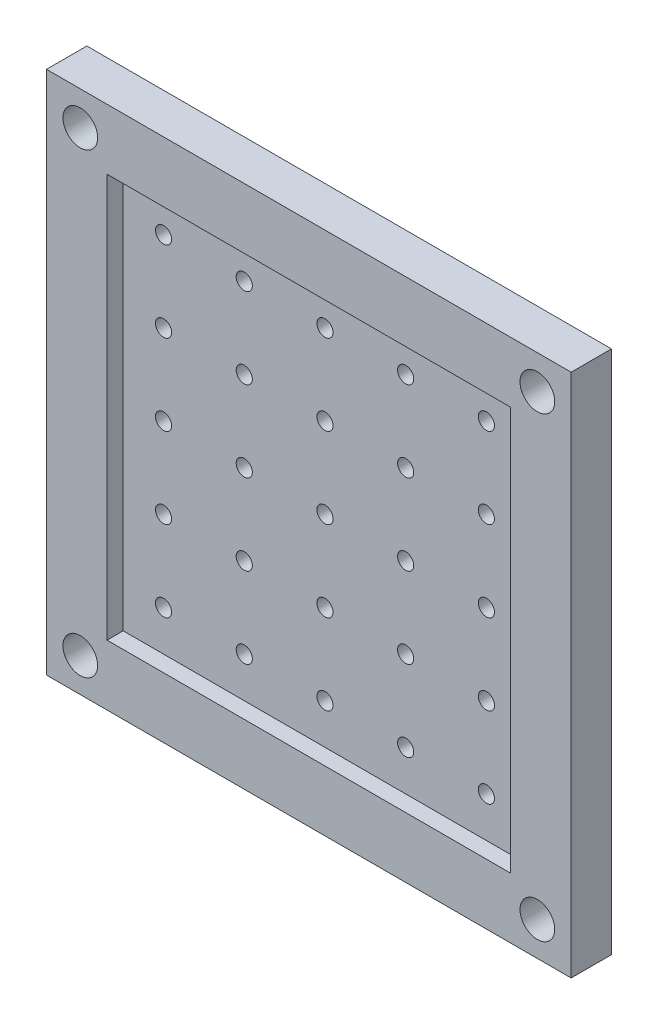
SolidWorks part; units mm, degrees
ref_plane "Front Plane" through (0, 0, 0) normal (0, 0, 1) x (1, 0, 0)
ref_plane "Top Plane" through (0, 0, 0) normal (0, 1, 0) x (1, 0, 0)
ref_plane "Right Plane" through (0, 0, 0) normal (1, 0, 0) x (0, 0, -1)
sketch "Sketch1" plane through (0, 0, 0) normal (0, 0, 1) x (1, 0, 0)
  line L1 (-32.5, -32.5) -> (32.5, -32.5)
  line L2 (-32.5, -32.5) -> (-32.5, 32.5)
  line L3 (-32.5, 32.5) -> (32.5, 32.5)
  line L4 (32.5, -32.5) -> (32.5, 32.5)
  line L5 (-32.5, -32.5) -> (32.5, 32.5) construction
  line L6 (-32.5, 32.5) -> (32.5, -32.5) construction
  line L7 (35, 35) -> (-35, 35) construction
  circle A9 centre (-28.3137, 28.3137) radius 2.15
  circle A10 centre (-28.3137, -28.3137) radius 2.15
  circle A11 centre (28.3137, -28.3137) radius 2.15
  circle A12 centre (28.3137, 28.3137) radius 2.15
  circle A13 centre (-28.3137, 28.3137) radius 1.85 construction
  point P0 (0, 0)
  dimension "D2" = 0.3
  dimension "D1" = 2.5
extrude "Boss-Extrude1" add sketch "Sketch1" along normal blind 3
sketch "Sketch2" plane through (0, 0, 3) normal (0, 0, 1) x (1, 0, 0)
  line L1 (-25, -25) -> (25, -25)
  line L2 (-25, -25) -> (-25, 25)
  line L3 (-25, 25) -> (25, 25)
  line L4 (32.5, -32.5) -> (32.5, 32.5)
  line L5 (32.5, 32.5) -> (-32.5, 32.5)
  line L6 (-32.5, 32.5) -> (-32.5, -32.5)
  line L7 (-32.5, -32.5) -> (32.5, -32.5)
  line L8 (32.5, -32.5) -> (32.5, 32.5)
  line L9 (32.5, 32.5) -> (-32.5, 32.5)
  line L10 (-32.5, 32.5) -> (-32.5, -32.5)
  line L11 (-32.5, -32.5) -> (32.5, -32.5)
  line L12 (25, -25) -> (25, 25)
  line L13 (-25, -25) -> (25, 25) construction
  line L14 (-25, 25) -> (25, -25) construction
  circle A3 centre (-28.3137, -28.3137) radius 2.15
  circle A4 centre (28.3137, -28.3137) radius 2.15
  circle A5 centre (-28.3137, 28.3137) radius 2.15
  circle A7 centre (28.3137, 28.3137) radius 2.15
  circle A8 centre (-28.3137, 28.3137) radius 2.15 construction
  point P2 (0, 0)
  dimension "D2" = 50
  dimension "D1" = 0
extrude "Boss-Extrude2" add sketch "Sketch2" along normal blind 2
sketch "Sketch3" plane through (0, 0, 3) normal (0, 0, 1) x (1, 0, 0)
  line L0 (-20, -25) -> (-20, -20) construction
  line L1 (-25, -25) -> (25, -25) construction
  line L2 (-20, -20) -> (-25, -20) construction
  line L3 (-25, 25) -> (-25, -25) construction
  line L4 (-10, -20) -> (-20, -20) construction
  line L5 (-20, -20) -> (-20, -10) construction
  line L6 (20, -20) -> (25, -20) construction
  line L7 (25, -25) -> (25, 25) construction
  line L8 (20, 20) -> (20, 25) construction
  line L9 (25, 25) -> (-25, 25) construction
  circle A0 centre (-20, -20) radius 1
  circle A1 centre (-10, -20) radius 1
  circle A2 centre (0, -20) radius 1
  circle A3 centre (10, -20) radius 1
  circle A4 centre (20, -20) radius 1
  circle A5 centre (-10, -10) radius 1
  circle A6 centre (0, -10) radius 1
  circle A7 centre (10, -10) radius 1
  circle A8 centre (20, -10) radius 1
  circle A9 centre (-10, 0) radius 1
  circle A10 centre (0, 0) radius 1
  circle A11 centre (10, 0) radius 1
  circle A12 centre (20, 0) radius 1
  circle A13 centre (-10, 10) radius 1
  circle A14 centre (0, 10) radius 1
  circle A15 centre (10, 10) radius 1
  circle A16 centre (20, 10) radius 1
  circle A17 centre (-10, 20) radius 1
  circle A18 centre (0, 20) radius 1
  circle A19 centre (10, 20) radius 1
  circle A20 centre (20, 20) radius 1
  circle A21 centre (-20, -10) radius 1
  circle A22 centre (-20, 0) radius 1
  circle A23 centre (-20, 10) radius 1
  circle A24 centre (-20, 20) radius 1
  dimension "D1" = 2
  dimension "D4" = 10
  dimension "D2" = 5
  dimension "D3" = 5
extrude "Cut-Extrude1" cut sketch "Sketch3" against normal through all
chamfer "Chamfer1" distance 1.5 angle 45 4 edges at (30.4637, -28.3137, 0) (30.4637, 28.3137, 0) (-26.1637, 28.3137, 0) (-26.1637, -28.3137, 0)
sketch "Sketch4" plane through (0, 0, 0) normal (0, 0, -1) x (-1, 0, 0)
  line L0 (-25, -25) -> (-25, 25) construction
  line L1 (25, -25) -> (-25, -25) construction
  line L2 (25, 25) -> (25, -25) construction
  line L3 (-25, 25) -> (25, 25) construction
  line L4 (-25, -25) -> (-25, 25)
  line L5 (25, -25) -> (-25, -25)
  line L6 (25, 25) -> (25, -25)
  line L7 (-25, 25) -> (25, 25)
extrude "Cut-Extrude2" cut sketch "Sketch4" against normal blind 1
